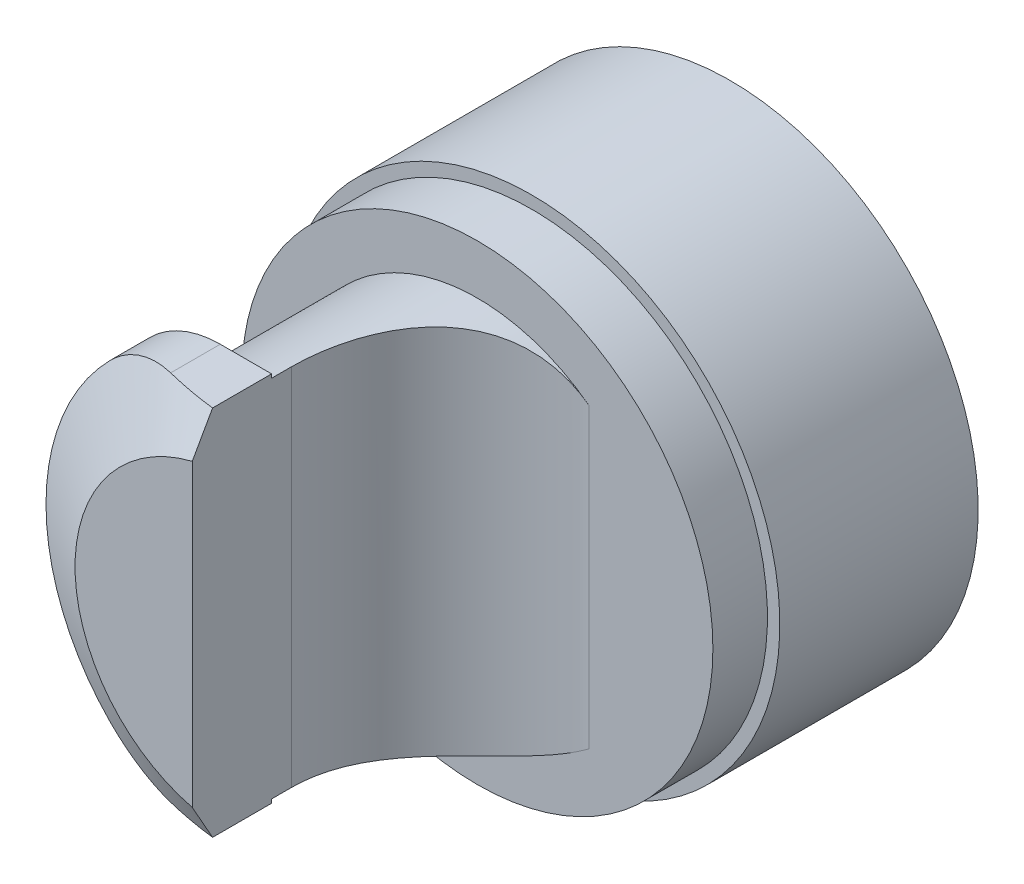
SolidWorks part; units mm, degrees
ref_plane "Front Plane" through (0, 0, 0) normal (0, 0, 1) x (1, 0, 0)
ref_plane "Top Plane" through (0, 0, 0) normal (0, 1, 0) x (1, 0, 0)
ref_plane "Right Plane" through (0, 0, 0) normal (1, 0, 0) x (0, 0, -1)
sketch "Sketch1" plane through (0, 0, 0) normal (0, 0, 1) x (1, 0, 0)
  circle A0 centre (0, 0) radius 2.375
  dimension "D1" = 4.75
extrude "Boss-Extrude1" add sketch "Sketch1" along normal blind 0.55
sketch "Sketch2" plane through (0, 0, 0.55) normal (0, 0, 1) x (1, 0, 0)
  circle A0 centre (0, 0) radius 1.875
  dimension "D1" = 3.75
extrude "Boss-Extrude2" add sketch "Sketch2" along normal blind 1.7
sketch "Sketch3" plane through (0, 0, 0) normal (0, 0, -1) x (-1, 0, 0)
  circle A0 centre (0, 0) radius 2.5
  dimension "D1" = 5
extrude "Boss-Extrude3" add sketch "Sketch3" along normal blind 2
sketch "Sketch4" plane through (0, 0, 2.25) normal (0, 0, 1) x (1, 0, 0)
  circle A0 centre (0, 0) radius 2.25
  dimension "D1" = 4.5
extrude "Boss-Extrude4" add sketch "Sketch4" along normal blind 0.8
sketch "Sketch5" plane through (0, 0, 3.05) normal (0, 0, 1) x (1, 0, 0)
  line L1 (-0.375, -3.0369) -> (0.375, -3.0369)
  line L2 (-0.375, -3.0369) -> (-0.375, 3.0369)
  line L3 (-0.375, 3.0369) -> (0.375, 3.0369)
  line L4 (0.375, -3.0369) -> (0.375, 3.0369)
  line L5 (-0.375, -3.0369) -> (0.375, 3.0369) construction
  line L6 (-0.375, 3.0369) -> (0.375, -3.0369) construction
  point P0 (0, 0)
  dimension "D1" = 0.75
extrude "Cut-Extrude1" cut sketch "Sketch5" against normal up to surface (2.5 mm away) up to face at (1.875, 0, 0.55)
chamfer "Chamfer1" distance 0.4 angle 60 2 edges at (-2.25, 0, 3.05) (2.25, 0, 3.05)
sketch "Sketch6" plane through (0, 0, 3.05) normal (0, 0, 1) x (1, 0, 0)
  line L1 (-3.2793, -1.875) -> (3.2793, -1.875)
  line L2 (-3.2793, -1.875) -> (-3.2793, 1.875)
  line L3 (-3.2793, 1.875) -> (3.2793, 1.875)
  line L4 (3.2793, -1.875) -> (3.2793, 1.875)
  line L5 (-3.2793, -1.875) -> (3.2793, 1.875) construction
  line L6 (-3.2793, 1.875) -> (3.2793, -1.875) construction
  line L7 (-3.4518, 2.624) -> (3.5474, 2.624)
  line L8 (-3.4518, 2.624) -> (-3.4518, -2.711)
  line L9 (-3.4518, -2.711) -> (3.5474, -2.711)
  line L10 (3.5474, 2.624) -> (3.5474, -2.711)
  point P0 (0, 0)
  dimension "D1" = 3.75
extrude "Cut-Extrude3" cut sketch "Sketch6" against normal blind 2
fillet "Fillet2" radius 1 4 edges at (-1.2437, 1.875, 2.45) (1.2437, 1.875, 2.45) (-1.2437, -1.875, 2.45) (1.2437, -1.875, 2.45)
sketch "Sketch7" plane through (0, 0, -2) normal (0, 0, -1) x (-1, 0, 0)
  circle A0 centre (0, 0) radius 1
  dimension "D1" = 2
extrude "Cut-Extrude4" cut sketch "Sketch7" against normal blind 2
sketch "Sketch8" plane through (0, 0, 0) normal (0, 1, 0) x (1, 0, 0)
  line L2 (-0.8927, -2.25) -> (-1.6068, -2.25) construction
  line L5 (-0.375, -2.25) -> (-0.375, -0.55) construction
  line L7 (-0.625, -1.25) -> (0, -1.25)
  line L8 (0, -1.25) -> (0, -2.25)
  line L9 (0, -2.25) -> (-0.625, -2.25)
  circle A0 centre (-0.625, -1.75) radius 0.5
  dimension "D1" = 1
  dimension "D2" = 0.5
  dimension "D3" = 0.25
sketch "Sketch9" plane through (0, 0, 0) normal (0, 1, 0) x (1, 0, 0)
  line L0 (-2.375, -0.55) -> (2.375, -0.55) construction
  line L1 (0, -0.55) -> (3.3094, -0.55)
  line L2 (0, -0.55) -> (0, -3.4709)
  line L3 (0, -3.4709) -> (3.3094, -3.4709)
  line L4 (3.3094, -0.55) -> (3.3094, -3.4709)
extrude "Cut-Extrude5" cut sketch "Sketch9" along normal blind 3 and the other way blind 10
fillet "Fillet3" radius 1.5 1 edges at (-0.375, 0, 0.55)
